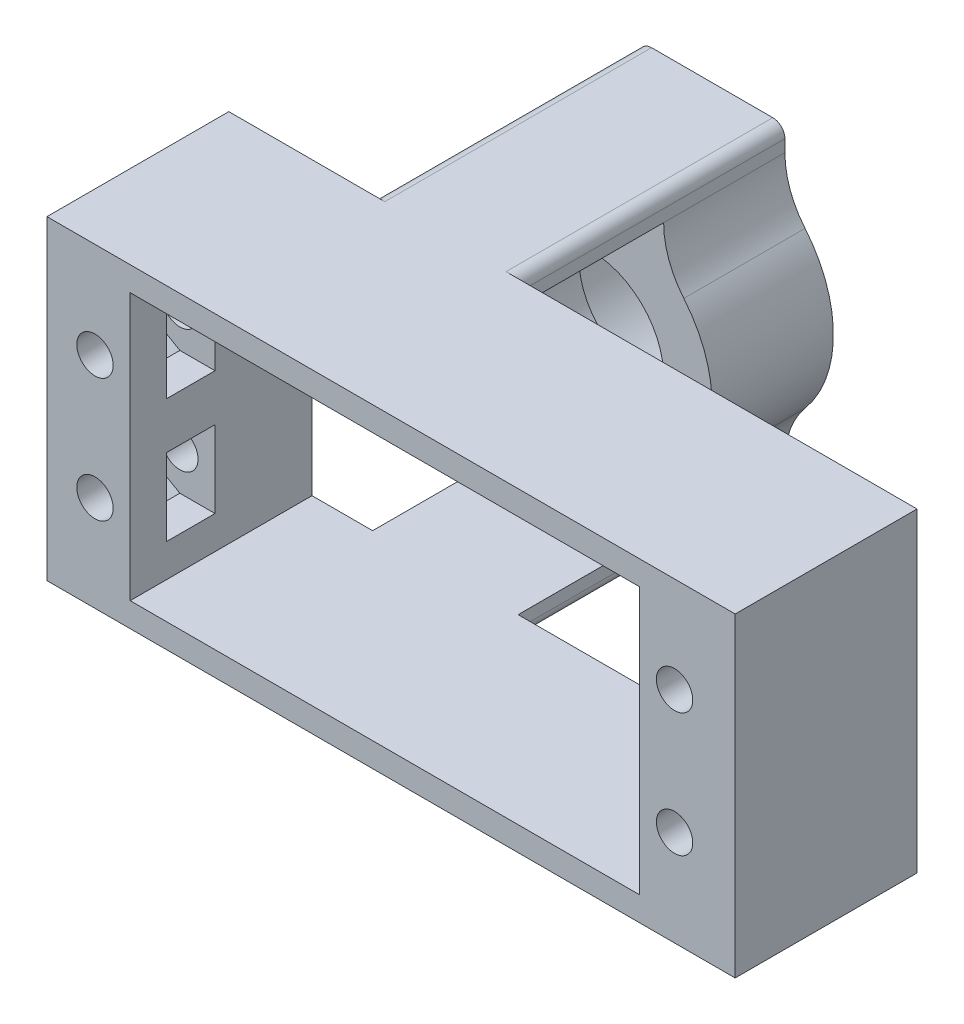
SolidWorks part; units mm, degrees
ref_plane "Plan de face" through (0, 0, 0) normal (0, 0, 1) x (1, 0, 0)
ref_plane "Plan de dessus" through (0, 0, 0) normal (0, 1, 0) x (1, 0, 0)
ref_plane "Plan de droite" through (0, 0, 0) normal (1, 0, 0) x (0, 0, -1)
sketch "Esquisse1" plane through (0, 0, 0) normal (0, 0, 1) x (1, 0, 0)
  line L1 (-23.2387, 9.5601) -> (56.7613, 9.5601)
  line L2 (-23.2387, 9.5601) -> (-23.2387, -16.4399)
  line L3 (-23.2387, -16.4399) -> (56.7613, -16.4399)
  line L4 (56.7613, 9.5601) -> (56.7613, -16.4399)
  dimension "D1" = 26
  dimension "D2" = 80
extrude "Boss.-Extru.1" add sketch "Esquisse1" along normal blind 5
sketch "Esquisse4" plane through (0, 0, 0) normal (0, 0, -1) x (-1, 0, 0)
  line L0 (23.2387, 9.5601) -> (23.2387, -16.4399) construction
  line L1 (38.2387, -13.9399) -> (23.2387, -13.9399)
  line L2 (38.2387, -13.9399) -> (38.2387, 7.0601)
  line L3 (38.2387, 7.0601) -> (23.2387, 7.0601)
  line L4 (23.2387, -13.9399) -> (23.2387, 7.0601)
  line L5 (23.2387, -16.4399) -> (-56.7613, -16.4399) construction
  line L6 (-56.7613, 9.5601) -> (23.2387, 9.5601) construction
  dimension "D1" = 0
  dimension "D2" = 2.5
  dimension "D3" = 2.5
  dimension "D4" = 15
extrude "Boss.-Extru.2" add sketch "Esquisse4" against normal blind 23
sketch "Esquisse6" plane through (0, -13.9399, 0) normal (0, -1, 0) x (1, 0, 0)
  line L0 (-23.2387, 23) -> (-23.2387, 5) construction
  line L1 (-23.2387, 0) -> (-38.2387, 0) construction
  circle A0 centre (-28.7387, 5) radius 1.9
  dimension "D2" = 5
  dimension "D3" = 3.8
  dimension "D1" = 5.5
extrude "Enlèv. mat.-Extru.1" cut sketch "Esquisse6" against normal blind 23
sketch "Esquisse7" plane through (0, 0, 23) normal (0, 0, 1) x (1, 0, 0)
  line L0 (-23.2387, 7.0601) -> (-23.2387, -13.9399) construction
  line L1 (-38.2387, 7.0601) -> (-23.2387, 7.0601) construction
  circle A0 centre (-33.2387, -3.4399) radius 2.5
  dimension "D1" = 5
  dimension "D2" = 10
  dimension "D3" = 10.5
extrude "Enlèv. mat.-Extru.2" cut sketch "Esquisse7" against normal blind 33
sketch "Esquisse8" plane through (0, 0, 0) normal (0, 0, -1) x (-1, 0, 0)
  line L0 (23.2387, -13.9399) -> (38.2387, -13.9399) construction
  line L1 (50.0831, -10.9399) -> (26.2387, -10.9399)
  line L2 (50.0831, -10.9399) -> (50.0831, 4.0601)
  line L3 (50.0831, 4.0601) -> (26.2387, 4.0601)
  line L4 (26.2387, -10.9399) -> (26.2387, 4.0601)
  line L5 (38.2387, 7.0601) -> (23.2387, 7.0601) construction
  line L6 (23.2387, -13.9399) -> (23.2387, -16.4399) construction
  dimension "D1" = 3
  dimension "D2" = 3
  dimension "D3" = 3
extrude "Enlèv. mat.-Extru.3" cut sketch "Esquisse8" against normal blind 20
sketch "Esquisse9" plane through (0, 0, 0) normal (0, 0, -1) x (-1, 0, 0)
  line L19 (38.2387, -13.9399) -> (38.2387, -10.9399)
  line L20 (38.2387, -10.9399) -> (26.2387, -10.9399)
  line L21 (26.2387, -10.9399) -> (26.2387, 4.0601)
  line L22 (26.2387, 4.0601) -> (38.2387, 4.0601)
  line L23 (38.2387, 4.0601) -> (38.2387, 7.0601)
  line L24 (38.2387, 7.0601) -> (23.2387, 7.0601)
  line L25 (23.2387, 7.0601) -> (23.2387, 9.5601)
  line L26 (23.2387, 9.5601) -> (-56.7613, 9.5601)
  line L27 (-56.7613, 9.5601) -> (-56.7613, -16.4399)
  line L28 (-56.7613, -16.4399) -> (23.2387, -16.4399)
  line L29 (23.2387, -16.4399) -> (23.2387, -13.9399)
  line L30 (23.2387, -13.9399) -> (38.2387, -13.9399)
  line L37 (23.2387, 7.0601) -> (23.2387, 9.5601)
  line L38 (23.2387, 9.5601) -> (17.8135, 9.5601)
  line L40 (17.8135, -16.4399) -> (23.2387, -16.4399)
  line L41 (23.2387, -16.4399) -> (23.2387, -13.9399)
  arc A3 (17.8135, -16.4399) -> (23.2387, -13.9399) centre (17.8135, -9.3033) ccw
  arc A4 (17.8135, 9.5601) -> (23.2387, 7.0601) centre (17.8135, 2.4236) cw
  dimension "D1" = 0
extrude "Enlèv. mat.-Extru.4" cut sketch "Esquisse9" against normal blind 20
sketch "Esquisse10" plane through (0, -13.9399, 0) normal (0, -1, 0) x (1, 0, 0)
  line L5 (-38.2387, 0) -> (-23.2387, 0)
  line L6 (-23.2387, 0) -> (-23.2387, 5)
  line L7 (-23.2387, 5) -> (-23.2387, 23)
  line L8 (-23.2387, 23) -> (-38.2387, 23)
  line L9 (-38.2387, 23) -> (-38.2387, 0)
  line L12 (-23.2387, 21.5) -> (-23.2387, 23)
  line L13 (-23.2387, 23) -> (-24.7387, 23)
  arc A0 (-23.2387, 21.5) -> (-24.7387, 23) centre (-24.7387, 21.5) ccw
  dimension "D2" = 3
  dimension "D1" = 0
extrude "Enlèv. mat.-Extru.5" cut sketch "Esquisse10" against normal blind 25
sketch "Esquisse12" plane through (0, -13.9399, 0) normal (0, -1, 0) x (1, 0, 0)
  line L0 (-24.7387, 23) -> (-38.2387, 23) construction
  line L1 (-38.2387, 23) -> (-36.7387, 23)
  line L2 (-38.2387, 23) -> (-38.2387, 21.5)
  arc A0 (-36.7387, 23) -> (-38.2387, 21.5) centre (-36.7387, 21.5) ccw
  dimension "D1" = 3
  dimension "D3" = 1.5
extrude "Enlèv. mat.-Extru.7" cut sketch "Esquisse12" against normal blind 25
sketch "Esquisse13" plane through (0, 7.0601, 0) normal (0, 1, 0) x (1, 0, 0)
  line L1 (-30.7594, -1.5) -> (-32.7801, -5)
  line L2 (-32.7801, -5) -> (-30.7594, -8.5)
  line L3 (-30.7594, -8.5) -> (-26.718, -8.5)
  line L4 (-26.718, -8.5) -> (-24.6972, -5)
  line L5 (-24.6972, -5) -> (-26.718, -1.5)
  line L6 (-26.718, -1.5) -> (-30.7594, -1.5)
  circle A0 centre (-28.7387, -5) radius 3.5 construction
  circle A1 centre (-28.7387, -5) radius 1.9 construction
  dimension "D1" = 7
extrude "Enlèv. mat.-Extru.8" cut sketch "Esquisse13" against normal blind 1
sketch "Esquisse14" plane through (0, 7.0601, 0) normal (0, 1, 0) x (1, 0, 0)
  line L0 (-30.7594, -1.5) -> (-32.7801, -5) construction
  line L1 (-26.718, -1.5) -> (-30.7594, -1.5) construction
  line L2 (-24.6972, -5) -> (-26.718, -1.5) construction
  line L3 (-26.718, -8.5) -> (-24.6972, -5) construction
  line L4 (-30.7594, -8.5) -> (-26.718, -8.5) construction
  line L6 (-25.8519, 0) -> (-31.6254, 0)
  line L7 (-31.6254, 0) -> (-34.5122, -5)
  line L8 (-34.5122, -5) -> (-31.6254, -10)
  line L9 (-31.6254, -10) -> (-25.8519, -10)
  line L15 (-32.7801, -5) -> (-30.7594, -8.5) construction
  line L16 (-30.7594, -1.5) -> (-32.7801, -5)
  line L17 (-26.718, -1.5) -> (-30.7594, -1.5)
  line L18 (-24.6972, -5) -> (-26.718, -1.5)
  line L19 (-26.718, -8.5) -> (-24.6972, -5)
  line L20 (-30.7594, -8.5) -> (-26.718, -8.5)
  line L21 (-32.7801, -5) -> (-30.7594, -8.5)
  line L22 (-25.8519, -10) -> (-23.2387, -5.4737)
  line L27 (-23.2387, -4.5263) -> (-25.8519, 0)
  line L28 (-38.2387, 0) -> (-23.2387, 0) construction
  line L29 (-23.2387, -4.5263) -> (-23.2387, -5.4737)
  line L30 (-23.2387, -21.5) -> (-23.2387, -5) construction
  circle A1 centre (-28.7387, -5) radius 5 construction
  circle A2 centre (-28.7387, -5) radius 1.9 construction
extrude "Boss.-Extru.3" add sketch "Esquisse14" along normal blind 2
sketch "Esquisse15" plane through (0, 0, 0) normal (0, 0, -1) x (-1, 0, 0)
  circle A7 centre (-51.7613, -8.5399) radius 1.5
  circle A8 centre (-51.7613, 1.6601) radius 1.5
  circle A9 centre (-3.9613, -8.5399) radius 1.5
  circle A10 centre (-3.9613, 1.6601) radius 1.5
  dimension "D10" = 3
extrude "Enlèv. mat.-Extru.9" cut sketch "Esquisse15" against normal blind 19
sketch "Esquisse17" plane through (0, 0, 5) normal (0, 0, 1) x (1, 0, 0)
  line L0 (56.7613, 9.5601) -> (-17.8135, 9.5601) construction
  line L1 (6.8613, 7.5601) -> (48.8613, 7.5601)
  line L2 (6.8613, 7.5601) -> (6.8613, -14.4399)
  line L3 (6.8613, -14.4399) -> (48.8613, -14.4399)
  line L4 (48.8613, 7.5601) -> (48.8613, -14.4399)
  circle A0 centre (3.9613, 1.6601) radius 1.5 construction
  dimension "D4" = 2.9
  dimension "D1" = 42
  dimension "D2" = 22
  dimension "D3" = 2
extrude "Enlèv. mat.-Extru.11" cut sketch "Esquisse17" against normal blind 19
sketch "Esquisse18" plane through (0, 0, 0) normal (0, 0, -1) x (-1, 0, 0)
  line L13 (-49.0113, 3.2479) -> (-51.7613, 4.8356)
  line L14 (-51.7613, 4.8356) -> (-54.5113, 3.2479)
  line L15 (-54.5113, 3.2479) -> (-54.5113, 0.0724)
  line L16 (-54.5113, 0.0724) -> (-51.7613, -1.5153)
  line L17 (-51.7613, -1.5153) -> (-49.0113, 0.0724)
  line L19 (-49.0113, -6.9521) -> (-51.7613, -5.3644)
  line L20 (-51.7613, -5.3644) -> (-54.5113, -6.9521)
  line L21 (-54.5113, -6.9521) -> (-54.5113, -10.1276)
  line L22 (-54.5113, -10.1276) -> (-51.7613, -11.7153)
  line L23 (-51.7613, -11.7153) -> (-49.0113, -10.1276)
  line L25 (-49.0113, -10.1276) -> (-46.2613, -8.5399)
  line L26 (-46.2613, -8.5399) -> (-49.0113, -6.9521)
  line L28 (-49.0113, 3.2479) -> (-46.2613, 1.6601)
  line L29 (-49.0113, 0.0724) -> (-46.2613, 1.6601)
  line L30 (-49.0113, -10.1276) -> (-49.0113, -8.5399) [skipped]
  line L31 (-49.0113, 0.0724) -> (-49.0113, 1.6601) [skipped]
  line L33 (-6.7113, 0.0724) -> (-9.4613, 1.6601)
  line L34 (-6.7113, 3.2479) -> (-9.4613, 1.6601)
  line L35 (-9.4613, -8.5399) -> (-6.7113, -6.9521)
  line L36 (-6.7113, -10.1276) -> (-9.4613, -8.5399)
  line L37 (-3.9613, -11.7153) -> (-6.7113, -10.1276)
  line L38 (-1.2113, -10.1276) -> (-3.9613, -11.7153)
  line L39 (-1.2113, -6.9521) -> (-1.2113, -10.1276)
  line L40 (-3.9613, -5.3644) -> (-1.2113, -6.9521)
  line L41 (-6.7113, -6.9521) -> (-3.9613, -5.3644)
  line L42 (-3.9613, -1.5153) -> (-6.7113, 0.0724)
  line L43 (-1.2113, 0.0724) -> (-3.9613, -1.5153)
  line L44 (-1.2113, 3.2479) -> (-1.2113, 0.0724)
  line L45 (-3.9613, 4.8356) -> (-1.2113, 3.2479)
  line L46 (-6.7113, 3.2479) -> (-3.9613, 4.8356)
  arc A0 (-5.3363, -6.1583) -> (-5.3363, -10.9214) centre (-3.9613, -8.5399) cw construction
  arc A1 (-5.3363, 4.0417) -> (-5.3363, -0.7214) centre (-3.9613, 1.6601) cw construction
  arc A2 (-50.3863, 4.0417) -> (-50.3863, -0.7214) centre (-51.7613, 1.6601) ccw construction
  arc A3 (-50.3863, -6.1583) -> (-50.3863, -10.9214) centre (-51.7613, -8.5399) ccw construction
  circle A6 centre (-51.7613, 1.6601) radius 1.5 construction
  circle A7 centre (-51.7613, -8.5399) radius 1.5 construction
  dimension "D1" = 5.5
  dimension "D2" = 5.5
extrude "Enlèv. mat.-Extru.12" cut sketch "Esquisse18" against normal blind 2
sketch "Esquisse19" plane through (0, 0, 0) normal (0, 0, -1) x (-1, 0, 0)
  line L9 (-12.8613, -16.4399) -> (-22.8613, -16.4399)
  line L12 (-11.8613, -15.4399) -> (-11.8613, -14.4399)
  line L13 (-11.8613, -14.4399) -> (-23.8613, -14.4399)
  line L21 (-23.8613, -15.4399) -> (-23.8613, -14.4399)
  line L22 (-6.8613, -10.041) -> (-6.8613, -14.4399) construction
  line L23 (-6.8613, -14.4399) -> (-48.8613, -14.4399) construction
  line L24 (17.8135, -16.4399) -> (-56.7613, -16.4399) construction
  line L27 (-23.8613, 8.5601) -> (-23.8613, 7.5601)
  line L28 (-11.8613, 7.5601) -> (-23.8613, 7.5601)
  line L29 (-11.8613, 8.5601) -> (-11.8613, 7.5601)
  line L30 (-12.8613, 9.5601) -> (-22.8613, 9.5601)
  arc A2 (-12.8613, -16.4399) -> (-11.8613, -15.4399) centre (-12.8613, -15.4399) ccw
  arc A3 (-23.8613, -15.4399) -> (-22.8613, -16.4399) centre (-22.8613, -15.4399) ccw
  arc A6 (-23.8613, 8.5601) -> (-22.8613, 9.5601) centre (-22.8613, 8.5601) cw
  arc A7 (-12.8613, 9.5601) -> (-11.8613, 8.5601) centre (-12.8613, 8.5601) cw
  point P4 (-17.8613, -16.4399)
  dimension "D3" = 0
  dimension "D4" = 0
  dimension "D5" = 2
  dimension "D1" = 10
  dimension "D2" = 11
  dimension "D6" = 2
extrude "Boss.-Extru.4" add sketch "Esquisse19" along normal blind 22
sketch "Esquisse23" plane through (0, 0, -22) normal (0, 0, -1) x (-1, 0, 0)
  line L0 (-6.8613, -10.041) -> (-6.8613, -14.4399) construction
  line L4 (-23.8613, 8.5601) -> (-23.8613, 7.5601)
  line L5 (-23.8613, 7.5601) -> (-11.8613, 7.5601)
  line L6 (-11.8613, 7.5601) -> (-11.8613, 8.5601)
  line L7 (-12.8613, 9.5601) -> (-22.8613, 9.5601)
  line L8 (-23.8613, 8.5601) -> (-23.8613, 7.5601)
  line L10 (-11.8613, 7.5601) -> (-11.8613, 8.5601)
  line L11 (-12.8613, 9.5601) -> (-22.8613, 9.5601)
  line L12 (-22.8613, -16.4399) -> (-12.8613, -16.4399)
  line L13 (-11.8613, -15.4399) -> (-11.8613, -14.4399)
  line L14 (-11.8613, -14.4399) -> (-23.8613, -14.4399)
  line L15 (-23.8613, -14.4399) -> (-23.8613, -15.4399)
  line L16 (-22.8613, -16.4399) -> (-12.8613, -16.4399)
  line L17 (-11.8613, -15.4399) -> (-11.8613, -14.4399)
  line L19 (-23.8613, -14.4399) -> (-23.8613, -15.4399)
  line L21 (-6.8613, -14.4399) -> (-11.8613, -14.4399) construction
  arc A0 (-10.1971, -9.8632) -> (-10.1971, 2.9835) centre (-17.8613, -3.4399) ccw
  arc A1 (-11.8613, 7.5601) -> (-10.1971, 2.9835) centre (-4.7363, 7.5601) ccw
  arc A2 (-22.8613, 9.5601) -> (-23.8613, 8.5601) centre (-22.8613, 8.5601) ccw
  arc A3 (-11.8613, 8.5601) -> (-12.8613, 9.5601) centre (-12.8613, 8.5601) ccw
  arc A4 (-22.8613, 9.5601) -> (-23.8613, 8.5601) centre (-22.8613, 8.5601) ccw
  arc A5 (-11.8613, 8.5601) -> (-12.8613, 9.5601) centre (-12.8613, 8.5601) ccw
  arc A6 (-23.8613, -15.4399) -> (-22.8613, -16.4399) centre (-22.8613, -15.4399) ccw
  arc A7 (-12.8613, -16.4399) -> (-11.8613, -15.4399) centre (-12.8613, -15.4399) ccw
  arc A8 (-23.8613, -15.4399) -> (-22.8613, -16.4399) centre (-22.8613, -15.4399) ccw
  arc A9 (-12.8613, -16.4399) -> (-11.8613, -15.4399) centre (-12.8613, -15.4399) ccw
  arc A10 (-23.8613, 7.5601) -> (-25.5255, 2.9835) centre (-30.9863, 7.5601) cw
  arc A11 (-23.8613, -14.4399) -> (-25.5255, -9.8632) centre (-30.9863, -14.4399) ccw
  arc A12 (-11.8613, -14.4399) -> (-10.1971, -9.8632) centre (-4.7363, -14.4399) cw
  arc A13 (-25.5255, 2.9835) -> (-25.5255, -9.8632) centre (-17.8613, -3.4399) ccw
  dimension "D3" = 20
  dimension "D5" = 11
  dimension "D4" = 11
  dimension "D1" = 0
  dimension "D2" = 0
extrude "Boss.-Extru.5" add sketch "Esquisse23" along normal blind 10
sketch "Esquisse25" plane through (0, 0, -32) normal (0, 0, -1) x (-1, 0, 0)
  circle A0 centre (-17.8613, -3.4399) radius 8
  arc A1 (-10.1971, -9.8632) -> (-10.1971, 2.9835) centre (-17.8613, -3.4399) ccw construction
  dimension "D1" = 16
extrude "Enlèv. mat.-Extru.13" cut sketch "Esquisse25" against normal blind 5
sketch "Esquisse26" plane through (0, 0, -27) normal (0, 0, -1) x (-1, 0, 0)
  circle A0 centre (-17.8613, -3.4399) radius 6
  circle A1 centre (-17.8613, -3.4399) radius 8 construction
  dimension "D1" = 12
extrude "Enlèv. mat.-Extru.14" cut sketch "Esquisse26" against normal blind 5
sketch "Esquisse33" plane through (0, 0, 0) normal (0, 0, -1) x (-1, 0, 0)
  line L0 (23.2387, -13.9399) -> (23.2387, 7.0601)
  line L5 (-56.7613, -16.4399) -> (-22.8613, -16.4399)
  line L20 (-22.8613, 9.5601) -> (-56.7613, 9.5601)
  line L23 (-56.7613, -16.4399) -> (-22.8613, -16.4399)
  line L24 (-23.8613, -15.4399) -> (-23.8613, -14.4399)
  line L25 (-23.8613, -15.4399) -> (-23.8613, -14.4399)
  line L26 (-23.8613, -14.4399) -> (-48.8613, -14.4399)
  line L27 (-23.8613, -14.4399) -> (-48.8613, -14.4399)
  line L28 (-48.8613, -14.4399) -> (-48.8613, -10.041)
  line L29 (-48.8613, -14.4399) -> (-48.8613, -10.041)
  line L30 (-48.8613, -10.041) -> (-51.7613, -11.7153)
  line L31 (-48.8613, -10.041) -> (-51.7613, -11.7153)
  line L32 (-51.7613, -11.7153) -> (-54.5113, -10.1276)
  line L33 (-51.7613, -11.7153) -> (-54.5113, -10.1276)
  line L34 (-11.8613, 8.5601) -> (-11.8613, 7.5601)
  line L35 (-11.8613, 7.5601) -> (-6.8613, 7.5601)
  line L36 (-6.8613, 7.5601) -> (-6.8613, 3.1612)
  line L37 (-6.8613, 3.1612) -> (-3.9613, 4.8356)
  line L38 (-3.9613, 4.8356) -> (-1.2113, 3.2479)
  line L39 (-1.2113, 3.2479) -> (-1.2113, 0.0724)
  line L40 (-1.2113, 0.0724) -> (-3.9613, -1.5153)
  line L41 (-3.9613, -1.5153) -> (-6.8613, 0.159)
  line L42 (-6.8613, 0.159) -> (-6.8613, -7.0388)
  line L43 (-6.8613, -7.0388) -> (-3.9613, -5.3644)
  line L44 (-3.9613, -5.3644) -> (-1.2113, -6.9521)
  line L45 (-1.2113, -6.9521) -> (-1.2113, -10.1276)
  line L46 (-1.2113, -10.1276) -> (-3.9613, -11.7153)
  line L47 (-3.9613, -11.7153) -> (-6.8613, -10.041)
  line L48 (-6.8613, -10.041) -> (-6.8613, -14.4399)
  line L49 (-6.8613, -14.4399) -> (-11.8613, -14.4399)
  line L50 (-11.8613, -14.4399) -> (-11.8613, -15.4399)
  line L51 (-12.8613, -16.4399) -> (17.8135, -16.4399)
  line L52 (23.2387, -13.9399) -> (38.2387, -13.9399)
  line L53 (-54.5113, -10.1276) -> (-54.5113, -6.9521)
  line L54 (-54.5113, -10.1276) -> (-54.5113, -6.9521)
  line L55 (-54.5113, -6.9521) -> (-51.7613, -5.3644)
  line L56 (-54.5113, -6.9521) -> (-51.7613, -5.3644)
  line L57 (38.2387, -13.9399) -> (38.2387, -10.9399)
  line L58 (38.2387, -10.9399) -> (26.2387, -10.9399)
  line L59 (26.2387, -10.9399) -> (26.2387, 4.0601)
  line L60 (26.2387, 4.0601) -> (38.2387, 4.0601)
  line L61 (38.2387, 4.0601) -> (38.2387, 7.0601)
  line L62 (38.2387, 7.0601) -> (31.6254, 7.0601)
  line L63 (31.6254, 7.0601) -> (31.6254, 9.0601)
  line L64 (31.6254, 9.0601) -> (25.8519, 9.0601)
  line L65 (25.8519, 9.0601) -> (25.8519, 7.0601)
  line L66 (25.8519, 7.0601) -> (23.2387, 7.0601)
  line L67 (17.8135, 9.5601) -> (-12.8613, 9.5601)
  line L68 (-11.8613, 8.5601) -> (-11.8613, 7.5601)
  line L69 (-11.8613, 7.5601) -> (-6.8613, 7.5601)
  line L70 (-6.8613, 7.5601) -> (-6.8613, 3.1612)
  line L71 (-6.8613, 3.1612) -> (-3.9613, 4.8356)
  line L72 (-3.9613, 4.8356) -> (-1.2113, 3.2479)
  line L73 (-1.2113, 3.2479) -> (-1.2113, 0.0724)
  line L74 (-1.2113, 0.0724) -> (-3.9613, -1.5153)
  line L75 (-3.9613, -1.5153) -> (-6.8613, 0.159)
  line L76 (-6.8613, 0.159) -> (-6.8613, -7.0388)
  line L77 (-6.8613, -7.0388) -> (-3.9613, -5.3644)
  line L78 (-3.9613, -5.3644) -> (-1.2113, -6.9521)
  line L79 (-1.2113, -6.9521) -> (-1.2113, -10.1276)
  line L80 (-1.2113, -10.1276) -> (-3.9613, -11.7153)
  line L81 (-3.9613, -11.7153) -> (-6.8613, -10.041)
  line L82 (-6.8613, -10.041) -> (-6.8613, -14.4399)
  line L83 (-6.8613, -14.4399) -> (-11.8613, -14.4399)
  line L84 (-11.8613, -14.4399) -> (-11.8613, -15.4399)
  line L85 (-12.8613, -16.4399) -> (17.8135, -16.4399)
  line L101 (17.8135, 9.5601) -> (-12.8613, 9.5601)
  line L102 (-51.7613, -5.3644) -> (-48.8613, -7.0388)
  line L103 (-51.7613, -5.3644) -> (-48.8613, -7.0388)
  line L104 (-48.8613, -7.0388) -> (-48.8613, 0.159)
  line L105 (-48.8613, 7.5601) -> (-23.8613, 7.5601)
  line L106 (-23.8613, 7.5601) -> (-23.8613, 8.5601)
  line L107 (-22.8613, 9.5601) -> (-56.7613, 9.5601)
  line L124 (-48.8613, 7.5601) -> (-23.8613, 7.5601)
  line L125 (-23.8613, 7.5601) -> (-23.8613, 8.5601)
  line L126 (-48.8613, -7.0388) -> (-48.8613, 0.159)
  line L127 (-48.8613, 0.159) -> (-51.7613, -1.5153)
  line L128 (-48.8613, 0.159) -> (-51.7613, -1.5153)
  line L129 (-51.7613, -1.5153) -> (-54.5113, 0.0724)
  line L130 (-51.7613, -1.5153) -> (-54.5113, 0.0724)
  line L131 (-54.5113, 0.0724) -> (-54.5113, 3.2479)
  line L132 (-54.5113, 0.0724) -> (-54.5113, 3.2479)
  line L133 (-54.5113, 3.2479) -> (-51.7613, 4.8356)
  line L134 (-54.5113, 3.2479) -> (-51.7613, 4.8356)
  line L135 (-51.7613, 4.8356) -> (-48.8613, 3.1612)
  line L136 (-51.7613, 4.8356) -> (-48.8613, 3.1612)
  line L137 (-48.8613, 3.1612) -> (-48.8613, 7.5601)
  line L138 (-48.8613, 3.1612) -> (-48.8613, 7.5601)
  line L140 (-56.7613, 9.5601) -> (-56.7613, -16.4399)
  line L141 (-56.7613, 9.5601) -> (-56.7613, -16.4399)
  arc A3 (-22.8613, 9.5601) -> (-23.8613, 8.5601) centre (-22.8613, 8.5601) ccw
  arc A4 (-12.8613, -16.4399) -> (-11.8613, -15.4399) centre (-12.8613, -15.4399) ccw
  arc A5 (17.8135, -16.4399) -> (23.2387, -13.9399) centre (17.8135, -9.3033) ccw
  arc A6 (23.2387, 7.0601) -> (17.8135, 9.5601) centre (17.8135, 2.4236) ccw
  arc A7 (-11.8613, 8.5601) -> (-12.8613, 9.5601) centre (-12.8613, 8.5601) ccw
  arc A8 (-12.8613, -16.4399) -> (-11.8613, -15.4399) centre (-12.8613, -15.4399) ccw
  arc A9 (17.8135, -16.4399) -> (23.2387, -13.9399) centre (17.8135, -9.3033) ccw
  arc A10 (23.2387, 7.0601) -> (17.8135, 9.5601) centre (17.8135, 2.4236) ccw
  arc A11 (-11.8613, 8.5601) -> (-12.8613, 9.5601) centre (-12.8613, 8.5601) ccw
  arc A14 (-22.8613, 9.5601) -> (-23.8613, 8.5601) centre (-22.8613, 8.5601) ccw
  arc A17 (-23.8613, -15.4399) -> (-22.8613, -16.4399) centre (-22.8613, -15.4399) ccw
  arc A18 (-23.8613, -15.4399) -> (-22.8613, -16.4399) centre (-22.8613, -15.4399) ccw
  dimension "D1" = 0
  dimension "D2" = 0
extrude "Boss.-Extru.7" add sketch "Esquisse33" along normal blind 10
sketch "Esquisse35" plane through (0, 0, -10) normal (0, 0, -1) x (-1, 0, 0)
  line L1 (-7.8212, 4.8356) -> (-3.9613, 4.8356)
  line L2 (-7.8212, 4.8356) -> (-7.8212, -1.5153)
  line L3 (-7.8212, -1.5153) -> (-3.9613, -1.5153)
  line L4 (-3.9613, 4.8356) -> (-3.9613, -1.5153)
  line L5 (-7.7177, -5.3644) -> (-3.9613, -5.3644)
  line L6 (-7.7177, -5.3644) -> (-7.7177, -11.7153)
  line L7 (-7.7177, -11.7153) -> (-3.9613, -11.7153)
  line L8 (-3.9613, -5.3644) -> (-3.9613, -11.7153)
  line L9 (-51.7613, 4.8356) -> (-40.9237, 4.8356)
  line L10 (-51.7613, 4.8356) -> (-51.7613, -1.5153)
  line L11 (-51.7613, -1.5153) -> (-40.9237, -1.5153)
  line L12 (-40.9237, 4.8356) -> (-40.9237, -1.5153)
  line L13 (-51.7613, -5.3644) -> (-43.3923, -5.3644)
  line L14 (-51.7613, -5.3644) -> (-51.7613, -11.7153)
  line L15 (-51.7613, -11.7153) -> (-43.3923, -11.7153)
  line L16 (-43.3923, -5.3644) -> (-43.3923, -11.7153)
extrude "Enlèv. mat.-Extru.17" cut sketch "Esquisse35" against normal blind 12
sketch "Esquisse37" plane through (0, 0, -10) normal (0, 0, -1) x (-1, 0, 0)
  line L0 (-6.8613, 7.5601) -> (-6.8613, 4.8356) construction
  line L2 (-55.5195, 1.4231) -> (-55.5195, -7.9209)
  line L4 (-48.8613, 4.8356) -> (-48.8613, -11.7153)
  line L5 (-6.8613, 9.5601) -> (1.4375, 9.5601)
  line L6 (-6.8613, 9.5601) -> (-6.8613, -16.4399)
  line L7 (-6.8613, -16.4399) -> (1.4375, -16.4399)
  line L8 (1.4375, 9.5601) -> (1.4375, -16.4399)
  line L9 (17.8135, 9.5601) -> (-12.8613, 9.5601) construction
  line L10 (-12.8613, -16.4399) -> (17.8135, -16.4399) construction
  line L13 (-48.8613, -5.3644) -> (-48.8613, -1.5153) construction
  line L14 (-52.6625, 4.8356) -> (-48.8613, 4.8356)
  line L15 (-52.6625, 4.8356) -> (-54.8921, 3.2973)
  line L16 (-54.8921, 3.2973) -> (-55.5195, 1.4231)
  line L17 (-55.5195, -7.9209) -> (-55.0665, -9.9321)
  line L18 (-53.3408, -11.7153) -> (-48.8613, -11.7153)
  line L19 (-55.0665, -9.9321) -> (-53.3408, -11.7153)
extrude "Boss.-Extru.8" add sketch "Esquisse37" against normal blind 8
sketch "Esquisse38" plane through (0, -13.9399, 0) normal (0, -1, 0) x (1, 0, 0)
  line L0 (-17.8135, 5) -> (56.7613, 5) construction
  line L1 (-23.2387, 21.5) -> (-23.2387, 5) construction
  line L2 (-23.2387, 21.5) -> (-23.2387, 5)
  line L3 (-23.2387, 5) -> (-6.7387, 5)
  arc A0 (-23.2387, 21.5) -> (-6.7387, 5) centre (-6.7387, 21.5) ccw
extrude "Boss.-Extru.9" add sketch "Esquisse38" against normal blind 21
sketch "Esquisse42" plane through (0, 0, 5) normal (0, 0, 1) x (1, 0, 0)
  circle A0 centre (3.9613, 1.6601) radius 1.5 construction
  circle A1 centre (3.9613, -8.5399) radius 1.5 construction
  circle A2 centre (3.9613, 1.6601) radius 1.5
  circle A3 centre (3.9613, -8.5399) radius 1.5
  circle A4 centre (51.7613, 1.6601) radius 1.5 construction
  circle A5 centre (51.7613, -8.5399) radius 1.5 construction
  circle A6 centre (51.7613, 1.6601) radius 1.5
  circle A7 centre (51.7613, -8.5399) radius 1.5
extrude "Enlèv. mat.-Extru.18" cut sketch "Esquisse42" against normal blind 10
sketch "Esquisse43" plane through (0, 0, 5) normal (0, 0, 1) x (1, 0, 0)
  line L0 (0, 9.5601) -> (0, -16.4399)
  line L1 (0, 9.5601) -> (-41.7705, 9.5601)
  line L2 (0, -16.4399) -> (-41.7705, -16.4399)
  line L3 (-41.7705, 9.5601) -> (-41.7705, -16.4399)
  line L4 (56.7613, 9.5601) -> (-17.8135, 9.5601) construction
  line L5 (-17.8135, -16.4399) -> (56.7613, -16.4399) construction
extrude "Enlèv. mat.-Extru.19" cut sketch "Esquisse43" against normal through all both and the other way through all
